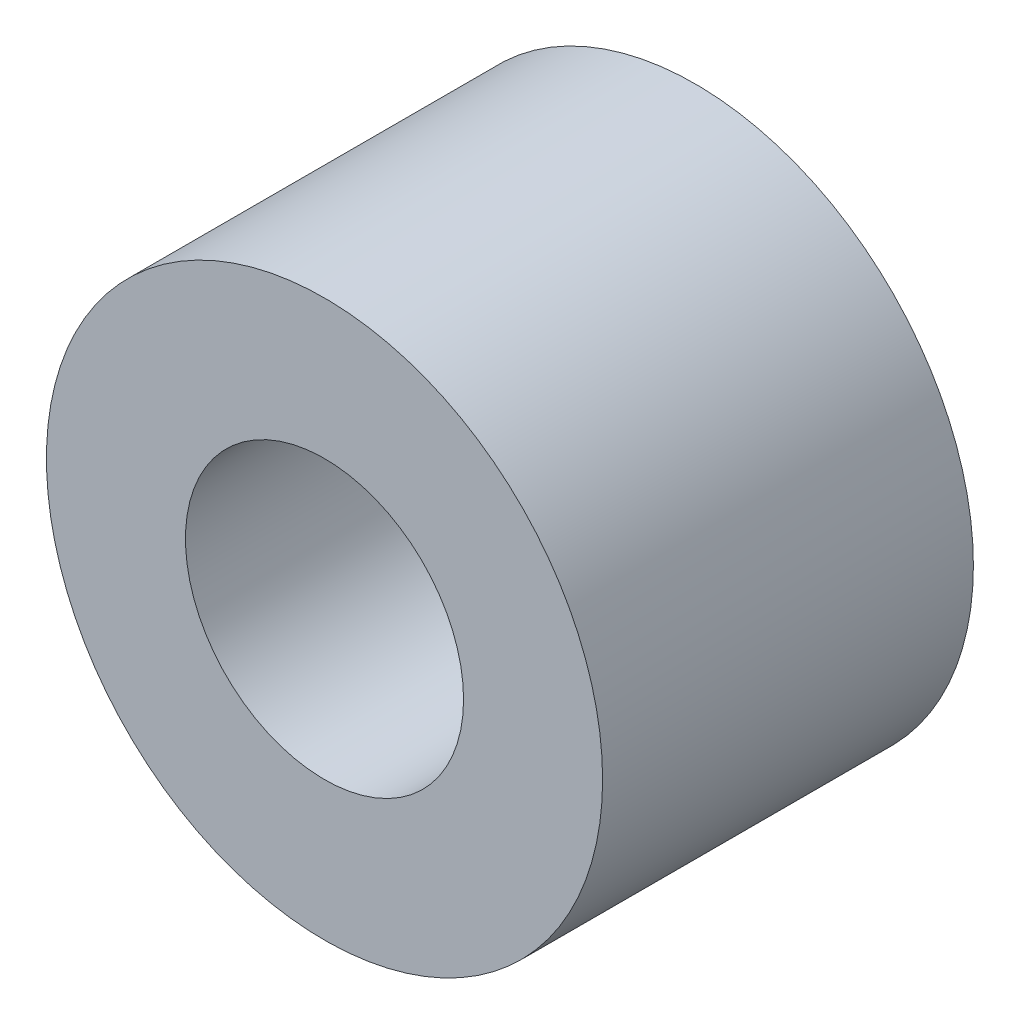
SolidWorks part; units mm, degrees
ref_plane "Front Plane" through (0, 0, 0) normal (0, 0, 1) x (1, 0, 0)
ref_plane "Top Plane" through (0, 0, 0) normal (0, 1, 0) x (1, 0, 0)
ref_plane "Right Plane" through (0, 0, 0) normal (1, 0, 0) x (0, 0, -1)
sketch "Sketch1" plane through (0, 0, 0) normal (0, 0, 1) x (1, 0, 0)
  circle A1 centre (-12.5, -45.6639) radius 1.5
  circle A2 centre (-12.5, -45.6639) radius 3
extrude "Boss-Extrude1" add sketch "Sketch1" against normal blind 4
